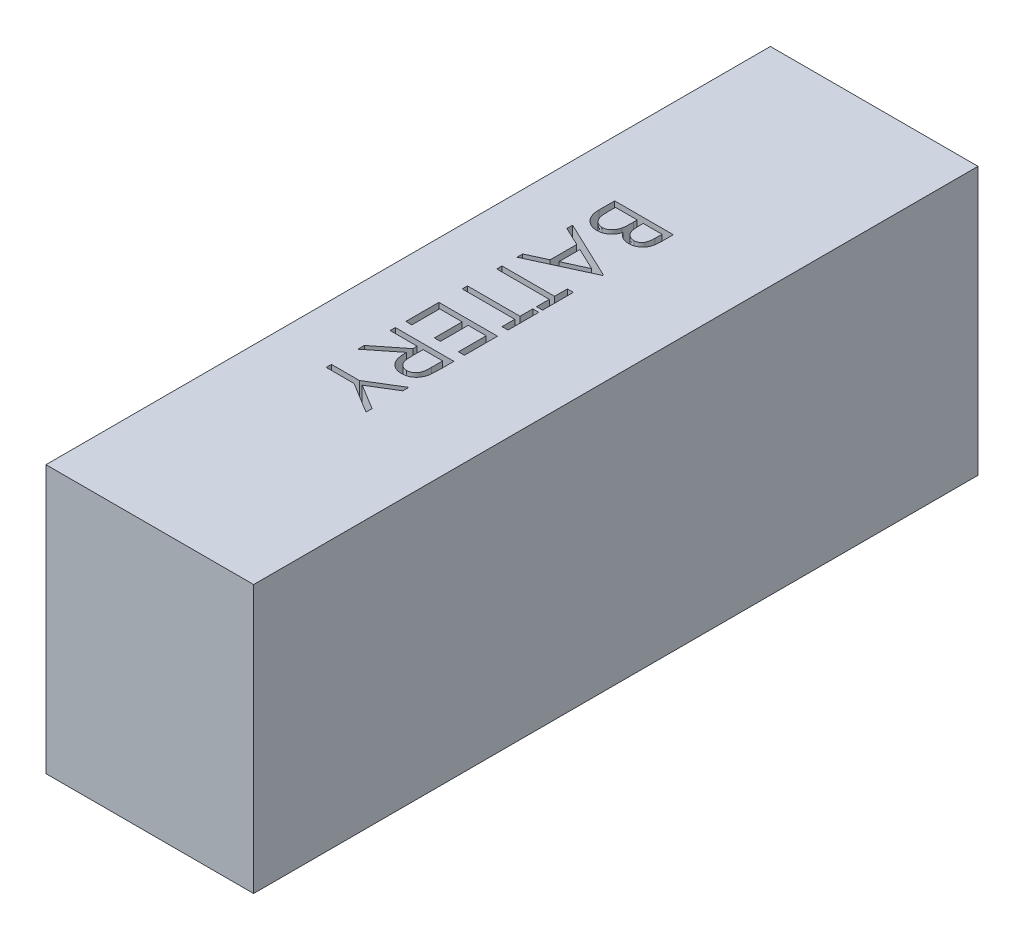
SolidWorks part; units mm, degrees
ref_plane "Front Plane" through (0, 0, 0) normal (0, 0, 1) x (1, 0, 0)
ref_plane "Top Plane" through (0, 0, 0) normal (0, 1, 0) x (1, 0, 0)
ref_plane "Right Plane" through (0, 0, 0) normal (1, 0, 0) x (0, 0, -1)
other "Center of Mass"
sketch "Sketch1" plane through (0, 0, 0) normal (0, 0, 1) x (1, 0, 0)
  line L1 (0, 0) -> (45, 0)
  line L2 (0, 0) -> (0, 58)
  line L3 (0, 58) -> (45, 58)
  line L4 (45, 0) -> (45, 58)
  dimension "D1" = 45
  dimension "D2" = 58
extrude "Boss-Extrude1" add sketch "Sketch1" against normal blind 157
sketch "Sketch2" plane through (0, 58, 0) normal (0, 1, 0) x (1, 0, 0)
  line L1 (12.1095, 157) -> (12.1095, 0) construction
  line L2 (45, 157) -> (0, 157) construction
  line L3 (45, 0) -> (0, 0) construction
  text T0 "BATTERY" font "Century Gothic" height in points 48
extrude "Cut-Extrude1" cut sketch "Sketch2" against normal blind 10
